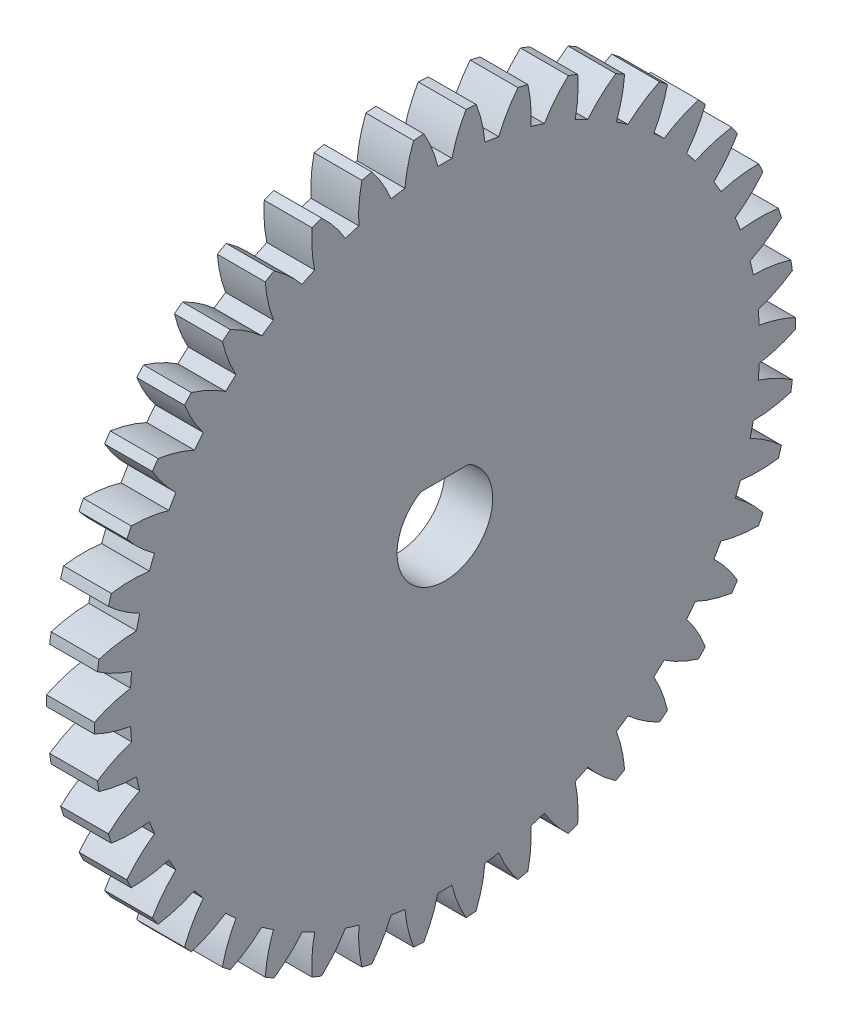
SolidWorks part; units mm, degrees
material "6061 Alloy"
ref_plane "Plane1" through (0, 0, 0) normal (0, 0, 1) x (1, 0, 0)
ref_plane "Plane2" through (0, 0, 0) normal (0, 1, 0) x (1, 0, 0)
ref_plane "Plane3" through (0, 0, 0) normal (1, 0, 0) x (0, 0, -1)
other "Configuration Table"
sketch "HoldingSke" plane through (0, 0, 0) normal (0, 1, 0) x (1, 0, 0)
  line L0 (0, 0) -> (0.3716, -0.3346)
  line L1 (-15, 0) -> (100, 0) construction
  line L2 (0, 0) -> (-2.1039, 2.3779)
  line L3 (0, 0) -> (-11.863, 4.5341)
  line L4 (0, 0) -> (6.4178, 5.7786)
  line L5 (0, 0) -> (-46.8476, -17.4728)
  line L6 (0, 0) -> (-4.9738, -3.3558)
  line L7 (-2.1039, 2.3779) -> (8.6586, 51.2059)
  line L8 (-76.2, 54.61) -> (-73.9, 54.61)
  line L9 (-71.009, 38.7566) -> (-53.1078, 45.2721)
  line L10 (-76.2, 71.12) -> (104.1128, 71.12)
  line L11 (0, 0) -> (-6, 0)
  line L12 (-76.2, 101.6) -> (-76.133, 101.6)
  line L13 (24.9733, 27.94) -> (52.9518, 28.4284)
  line L14 (24.9733, 27.94) -> (24.9743, 27.94)
  line L15 (24.9733, 27.94) -> (100.4006, 29.5858)
  line L16 (-63.627, -2) -> (-12.827, -2)
  circle A0 centre (0, 0) radius 6
  circle A1 centre (0, 0) radius 37.5
  circle A2 centre (0, 0) radius 37.5
  circle A3 centre (0, 0) radius 6
  dimension "MHD" = 75
  dimension "Hub_dia" = 75
  dimension "Bore" = 12
  dimension "MBD" = 12
  dimension "Num_teeth" = 42
  dimension "Pitch" = 0.5
  dimension "Overall_len" = 50
  dimension "Show_teeth" = 42
  dimension "Thickness" = 6
  dimension "OAL" = 50.0001
  dimension "T_dim" = 2.3
  dimension "Ap" = 20
  dimension "H" = 19.05
  dimension "Pitch_radius" = 180.3128
  dimension "Width" = 6
  dimension "Backlash" = 0.067
  dimension "Addendum_fac" = 1
  dimension "Dedendum_fac" = 1.25
  dimension "Clearance_fac" = 0.25
  dimension "Dedendum_add" = 0.001
  dimension "Module" = 2
sketch "BasProSke" plane through (0, 0, 0) normal (0, 1, 0) x (1, 0, 0)
  line L0 (-10, 0) -> (60, 0) construction
  line L1 (0, 0) -> (0, 44)
  line L2 (0, 0) -> (6, 0)
  line L3 (6, 0) -> (6, 44)
  line L4 (6, 44) -> (0, 44)
  dimension "Thickness" = 6
  dimension "Diameter" = 88
revolve "Base-Revolve" add sketch "BasProSke" angle 360 about L0
sketch "TooCutSke" plane through (0, 0, 0) normal (1, 0, 0) x (0, 0, -1)
  line L1 (0, 0) -> (0, 107) construction
  line L2 (0, 0) -> (-1.6877, 41.9661) construction
  line L3 (0, 0) -> (-6.2736, 83.715) construction
  line L4 (-1.6877, 41.9661) -> (-3.1368, 41.8575) construction
  arc A0 (0.8776, 39.4892) -> (-0.8776, 39.4892) centre (0, 0) ccw
  arc A1 (2.6666, 43.9446) -> (-2.6666, 43.9446) centre (0, 0) ccw
  circle A2 centre (0, 0) radius 42 construction
  circle A3 centre (0, 0) radius 39.4671 construction
  arc A4 (-0.8776, 39.4892) -> (-2.6666, 43.9446) centre (-17.2022, 35.5209) ccw
  arc A5 (2.6666, 43.9446) -> (0.8776, 39.4892) centre (17.2022, 35.5209) ccw
  dimension "Root_dia" = 78.998
  dimension "Overcut_dia" = 88.0508
  dimension "Pitch_dia" = 84
  dimension "Base_dia" = 78.9342
  dimension "Flank_rad" = 16.8
  dimension "Half_ang" = 4.286
  dimension "Half_CT" = 1.4532
extrude "ToothCut" cut sketch "TooCutSke" along normal through all
fillet "Breaks" [suppressed] radius 0.04
fillet "RootFillets" [suppressed] radius 0.501
pattern_circular "TeethCuts" count 42 every 8.571 about axis through (-10, 0, 0) along (1, 0, 0) of "ToothCut"
sketch "HubNeaOneSke" plane through (0, 0, 0) normal (-1, 0, 0) x (0, 0, 1)
  circle A0 centre (0, 0) radius 37.5
  dimension "Diameter" = 75
extrude "HubNearOne" [suppressed] add sketch "HubNeaOneSke" along normal blind 44.0001
sketch "HubNeaBotSke" plane through (0, 0, 0) normal (-1, 0, 0) x (0, 0, 1)
  circle A0 centre (0, 0) radius 37.5
  dimension "Diameter" = 75
extrude "HubNearBoth" [suppressed] add sketch "HubNeaBotSke" along normal blind 22
ref_plane "FarPln" through (6, 0, 0) normal (1, 0, 0) x (0, 0, -1)
sketch "HubFarSke" plane through (6, 0, 0) normal (1, 0, 0) x (0, 0, -1)
  circle A0 centre (0, 0) radius 37.5
  dimension "Diameter" = 75
extrude "HubFar" [suppressed] add sketch "HubFarSke" along normal blind 22
sketch "BorSke" plane through (0, 0, 0) normal (1, 0, 0) x (0, 0, -1)
  circle A0 centre (0, 0) radius 6
  dimension "Diameter" = 12
extrude "Bore" cut sketch "BorSke" along normal mid plane 100.0001
sketch "KeySke" plane through (0, 0, 0) normal (1, 0, 0) x (0, 0, -1)
  line L0 (-2.5, 0) -> (-2.5, 8.3)
  line L1 (-2.5, 8.3) -> (2.5, 8.3)
  line L2 (2.5, 8.3) -> (2.5, 0)
  line L3 (0, 0) -> (0, 34) construction
  line L4 (-2.5, 0) -> (2.5, 0)
  dimension "Offset" = 8.3
  dimension "Width" = 5
extrude "Keyway" [suppressed] cut sketch "KeySke" along normal mid plane 100.0001
pattern_circular "Keyway2" [suppressed] count 2 every 90 about axis through (-10, 0, 0) along (1, 0, 0)
sketch "Sketch1" plane through (6, 0, 0) normal (1, 0, 0) x (0, 0, -1)
  line L0 (3, 5.1962) -> (-3, 5.1962)
  circle A0 centre (0, 0) radius 6 construction
  circle A1 centre (0, 0) radius 6
  circle A2 centre (0, 0) radius 6
  arc A3 (-3, 5.1962) -> (3, 5.1962) centre (0, 0) ccw
  dimension "D1" = 6
  dimension "D2" = 0
extrude "Boss-Extrude2" add sketch "Sketch1" against normal up to surface (6 mm away) contours L0 A1 up to face at (0, 0, -6)
equation "' \"Module@HoldingSke\" = 6.35"
equation "' \"Num_teeth@HoldingSke\" = 12"
equation "' \"Ap@HoldingSke\" =  20"
equation "' \"Ap@HoldingSke\" = 20"
equation "' \"Width@HoldingSke\" = 0.5 * 25.4"
equation "' \"Hub_dia@HoldingSke\"= 1 * 25.4"
equation "' \"Hub_dia@HoldingSke\" = 1 * 25.4"
equation "' \"Overall_len@HoldingSke\" = 1.0 * 25.4"
equation "' \"Bore@HoldingSke\" = 0.75 * 25.4"
equation "' \"T_dim@HoldingSke\" = 0.1 * 25.4"
equation "' \"Width@KeySke\" = 0.25 * 25.4"
equation "' \"Show_teeth@HoldingSke\" = 13"
equation "' \"Backlash@HoldingSke\" = 0.009 * 25.4"
equation "' \"Addendum_fac@HoldingSke\" = 1.0"
equation "' \"Dedendum_fac@HoldingSke\" = 1.25"
equation "' \"Dedendum_add@HoldingSke\" = 0.00005 * 25.4"
equation "' \"Clearance_fac@HoldingSke\" = 0.25"
equation "\"Pitch@HoldingSke\" = 1 / \"Module@HoldingSke\""
equation "\"Overcut_dia@TooCutSke\" = (\"Num_teeth@HoldingSke\" + 2 * \"Addendum_fac@HoldingSke\") / \"Pitch@HoldingSke\" + 0.002 * 25.4"
equation "\"Pitch_dia@TooCutSke\" = \"Num_teeth@HoldingSke\" / \"Pitch@HoldingSke\""
equation "\"Base_dia@TooCutSke\" = \"Num_teeth@HoldingSke\" / \"Pitch@HoldingSke\" * cos((\"Ap@HoldingSke\"  * 3.14159265 / 180))"
equation "\"Root_dia@TooCutSke\" = (\"Num_teeth@HoldingSke\" + 2) / \"Pitch@HoldingSke\" - 2 * (\"Addendum_fac@HoldingSke\" + \"Dedendum_fac@HoldingSke\") / \"Pitch@HoldingSke\" - \"Dedendum_add@HoldingSke\" * 2"
equation "\"Half_ang@TooCutSke\" = 180 / \"Num_teeth@HoldingSke\""
equation "\"Half_CT@TooCutSke\" = \"Num_teeth@HoldingSke\" / \"Pitch@HoldingSke\" * sin((3.14159265 / 2 / \"Num_teeth@HoldingSke\")) / 2 - 7 * \"Backlash@HoldingSke\" / 4"
equation "\"Flank_rad@TooCutSke\" = \"Num_teeth@HoldingSke\" / \"Pitch@HoldingSke\" / 5"
equation "\"Radius@RootFillets\" = \"Clearance_fac@HoldingSke\" / \"Pitch@HoldingSke\" + \"Dedendum_add@HoldingSke\""
equation "\"Break_rad@Breaks\" = 0.02 / \"Pitch@HoldingSke\""
equation "\"Thickness@HoldingSke\" = \"Width@HoldingSke\""
equation "\"OAL@HoldingSke\" = \"Thickness@HoldingSke\""
equation "\"MHD@HoldingSke\" = (\"Num_teeth@HoldingSke\" + 2) / \"Pitch@HoldingSke\" - 2 * (\"Addendum_fac@HoldingSke\" + \"Dedendum_fac@HoldingSke\")  / \"Pitch@HoldingSke\" - \"Dedendum_add@HoldingSke\" * 2"
equation "\"MBD@HoldingSke\" = (\"Num_teeth@HoldingSke\" + 2) / \"Pitch@HoldingSke\" - 2 * (\"Addendum_fac@HoldingSke\" + \"Dedendum_fac@HoldingSke\")  / \"Pitch@HoldingSke\" - \"Dedendum_add@HoldingSke\" * 2 - 0.002 * 25.4"
equation "\"MHD@HoldingSke\" = ((sgn( \"MHD@HoldingSke\" - \"Hub_dia@HoldingSke\" )-1)*( \"MHD@HoldingSke\" - \"Hub_dia@HoldingSke\" ))/-2+ \"Hub_dia@HoldingSke\""
equation "\"MBD@HoldingSke\" = ((sgn( \"MBD@HoldingSke\" - \"Bore@HoldingSke\" )-1)*( \"MBD@HoldingSke\" - \"Bore@HoldingSke\" ))/-2+ \"Bore@HoldingSke\""
equation "\"OAL@HoldingSke\" = ((sgn( \"OAL@HoldingSke\" - \"Overall_len@HoldingSke\" )+1)*( \"OAL@HoldingSke\" - \"Overall_len@HoldingSke\" ))/2 + \"Overall_len@HoldingSke\" + 0.000002 * 25.4"
equation "\"Num_teeth@TeethCuts\" = int( \"Show_teeth@HoldingSke\" ) + 1"
equation "\"Num_teeth@TeethCuts\" = ((sgn( \"Num_teeth@TeethCuts\" - \"Num_teeth@HoldingSke\" )-1)*( \"Num_teeth@TeethCuts\" - \"Num_teeth@HoldingSke\" ))/-2+ \"Num_teeth@HoldingSke\""
equation "\"Num_teeth@TeethCuts\" = ((sgn( \"Num_teeth@TeethCuts\" - 2.0)+1)*( \"Num_teeth@TeethCuts\" - 2.0))/2 +2.0"
equation "\"Angle@TeethCuts\" = 360.0 / \"Num_teeth@HoldingSke\""
equation "\"Diameter@BasProSke\" = (\"Num_teeth@HoldingSke\" + 2 * \"Addendum_fac@HoldingSke\") / \"Pitch@HoldingSke\""
equation "\"Thickness@BasProSke\"  = \"Thickness@HoldingSke\""
equation "' \"Fillet_rad@BasProSke\" =  \"Thickness@HoldingSke\" * 0.05"
equation "' \"Fillet_rad@BasProSke\" = \"Thickness@HoldingSke\" * 0.05"
equation "\"MHD@HoldingSke\" = ((sgn( \"MHD@HoldingSke\" - \"Root_dia@TooCutSke\" )-1)*( \"MHD@HoldingSke\" - \"Root_dia@TooCutSke\" ))/-2+ \"Root_dia@TooCutSke\""
equation "\"Diameter@HubNeaOneSke\" = \"MHD@HoldingSke\""
equation "\"Length@HubNearOne\" = \"OAL@HoldingSke\" - \"Thickness@BasProSke\""
equation "\"Diameter@HubNeaBotSke\" = \"MHD@HoldingSke\""
equation "\"Length@HubNearBoth\" = ( \"OAL@HoldingSke\" - \"Thickness@BasProSke\" ) / 2.0"
equation "\"Thickness@FarPln\" = \"Thickness@BasProSke\""
equation "\"Diameter@HubFarSke\" = \"MHD@HoldingSke\""
equation "\"Length@HubFar\" = ( \"OAL@HoldingSke\" - \"Thickness@BasProSke\" ) / 2.0"
equation "\"Diameter@BorSke\" = \"MBD@HoldingSke\""
equation "\"D1@Bore\" = \"OAL@HoldingSke\" * 2.0"
equation "\"D1@Keyway\" = \"OAL@HoldingSke\" * 2.0"
equation "\"Offset@KeySke\" = \"T_dim@HoldingSke\" + \"MBD@HoldingSke\" / 2.0"
